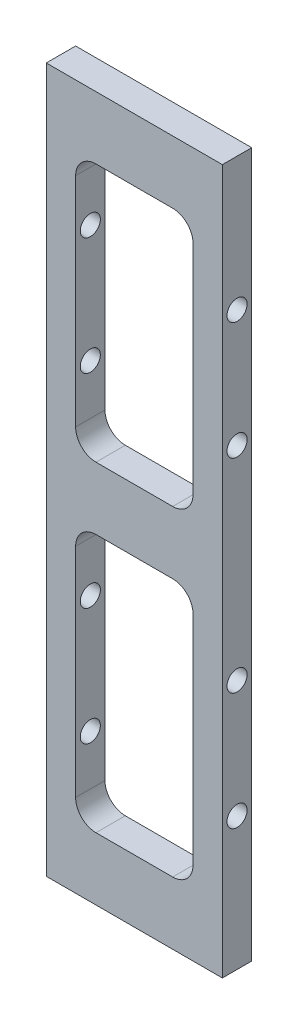
SolidWorks part; units mm, degrees
material "6061-T6 (SS)"
ref_plane "Front Plane" through (0, 0, 0) normal (0, 0, 1) x (1, 0, 0)
ref_plane "Top Plane" through (0, 0, 0) normal (0, 1, 0) x (1, 0, 0)
ref_plane "Right Plane" through (0, 0, 0) normal (1, 0, 0) x (0, 0, -1)
sketch "Sketch1" plane through (0, 0, 0) normal (0, 0, 1) x (1, 0, 0)
  line L1 (-14.2875, -57.15) -> (14.2875, -57.15)
  line L2 (-14.2875, -57.15) -> (-14.2875, 57.15)
  line L3 (-14.2875, 57.15) -> (14.2875, 57.15)
  line L4 (14.2875, -57.15) -> (14.2875, 57.15)
  line L5 (-14.2875, -57.15) -> (14.2875, 57.15) construction
  line L6 (-14.2875, 57.15) -> (14.2875, -57.15) construction
  point P0 (0, 0)
  dimension "D1" = 28.575
  dimension "D2" = 114.3
extrude "Boss-Extrude1" add sketch "Sketch1" along normal blind 4.7625
sketch "Sketch2" plane through (0, 0, 4.7625) normal (0, 0, 1) x (1, 0, 0)
  line L0 (-14.2875, 0) -> (14.2875, 0) construction
  line L1 (-14.2875, 57.15) -> (-14.2875, -57.15) construction
  line L2 (14.2875, -57.15) -> (14.2875, 57.15) construction
  line L3 (0, 57.15) -> (0, 0) construction
  line L4 (14.2875, 57.15) -> (-14.2875, 57.15) construction
  line L5 (-9.525, -46.99) -> (9.525, -5.08) construction
  line L6 (-9.525, 5.08) -> (9.525, 5.08)
  line L7 (-9.525, 5.08) -> (-9.525, 46.99)
  line L8 (-9.525, 46.99) -> (9.525, 46.99)
  line L9 (9.525, 5.08) -> (9.525, 46.99)
  line L10 (-9.525, 5.08) -> (9.525, 46.99) construction
  line L11 (-9.525, 46.99) -> (9.525, 5.08) construction
  line L12 (-9.525, -5.08) -> (9.525, -46.99) construction
  line L13 (9.525, -5.08) -> (9.525, -46.99)
  line L14 (-9.525, -46.99) -> (9.525, -46.99)
  line L15 (-9.525, -5.08) -> (-9.525, -46.99)
  line L16 (-9.525, -5.08) -> (9.525, -5.08)
  point P11 (0, 26.035)
  point P20 (0, -26.035)
  dimension "D1" = 4.7625
  dimension "D2" = 5.08
  dimension "D3" = 10.16
extrude "Cut-Extrude1" cut sketch "Sketch2" against normal through all
fillet "Fillet1" radius 3.302 8 edges at (-9.525, -46.99, 2.3813) (9.525, -46.99, 2.3813) (-9.525, -5.08, 2.3813) (9.525, -5.08, 2.3813) (-9.525, 5.08, 2.3813) (9.525, 5.08, 2.3813) (9.525, 46.99, 2.3813) (-9.525, 46.99, 2.3813)
hole_wizard "#4 Clearance Hole1" positions "Sketch4" profile "Sketch5" hole size "#4" standard "ANSI Inch" end condition through all
sketch "Sketch4" plane through (14.2875, 0, 0) normal (1, 0, 0) x (0, 0, -1)
  line L0 (-2.3813, 57.15) -> (-2.3813, -57.15) construction
  line L1 (-4.7625, 57.15) -> (0, 57.15) construction
  line L2 (-4.7625, -57.15) -> (0, -57.15) construction
  line L3 (0, -57.15) -> (0, 57.15) construction
  point P9 (-2.3812, 35.56)
  point P23 (-2.3812, 16.51)
  point P29 (-2.3812, -16.51)
  point P31 (-2.3812, -35.56)
  point P44 (0, 0)
  dimension "D1" = 19.05
  dimension "D2" = 16.51
  dimension "D3" = 16.51
  dimension "D4" = 19.05
sketch "Sketch5" plane through (14.2875, 35.56, 2.3812) normal (0, 1, 0) x (0, 0, -1)
  line L0 (0, 0) -> (0, 28.575)
  line L1 (0, 28.575) -> (1.6319, 28.575)
  line L2 (1.6319, 28.575) -> (1.6319, 0)
  line L5 (1.6319, 0) -> (0, 0)
  line L11 (0, -6.35) -> (0, 107.95) construction
  dimension "Thru Hole Dia." = 3.2639
  dimension "Thru Hole Depth" = 28.575
